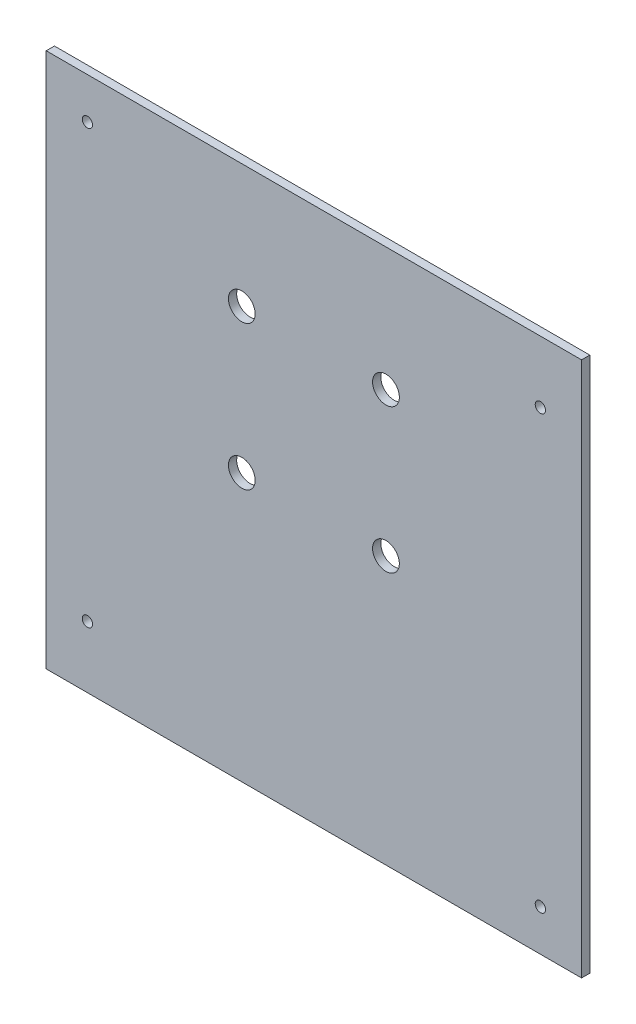
SolidWorks part; units mm, degrees
ref_plane "Спереди" through (0, 0, 0) normal (0, 0, 1) x (1, 0, 0)
ref_plane "Сверху" through (0, 0, 0) normal (0, 1, 0) x (1, 0, 0)
ref_plane "Справа" through (0, 0, 0) normal (1, 0, 0) x (0, 0, -1)
sketch "Эскиз1" plane through (0, 0, 0) normal (0, 0, 1) x (1, 0, 0)
  line L1 (-65, -82.5) -> (65, -82.5)
  line L2 (-65, -82.5) -> (-65, 47.5)
  line L3 (-65, 47.5) -> (65, 47.5)
  line L4 (65, -82.5) -> (65, 47.5)
  circle A0 centre (-55, 37.5) radius 1.25
  circle A1 centre (55, 32.5) radius 1.25
  circle A2 centre (55, -72.5) radius 1.25
  circle A3 centre (-55, -67.5) radius 1.25
  circle A4 centre (-17.5, 17.5) radius 3.25
  circle A5 centre (17.5, 17.5) radius 3.25
  circle A6 centre (-17.5, -17.5) radius 3.25
  circle A7 centre (17.5, -17.5) radius 3.25
  point P0 (0, 0)
  dimension "D3" = 2.5
  dimension "D4" = 2.5
  dimension "D5" = 2.5
  dimension "D6" = 2.5
  dimension "D8" = 10
  dimension "D9" = 10
  dimension "D11" = 10
  dimension "D12" = 10
  dimension "D13" = 10
  dimension "D14" = 15
  dimension "D15" = 35
  dimension "D16" = 35
  dimension "D17" = 6.5
  dimension "D18" = 6.5
  dimension "D19" = 6.5
  dimension "D20" = 6.5
  dimension "D21" = 35
  dimension "D22" = 35
  dimension "D23" = 47.5
  dimension "D24" = 47.5
  dimension "D25" = 30
  dimension "D26" = 47.5
  dimension "D1" = 130
  dimension "D2" = 130
  dimension "D7" = 10
  dimension "D10" = 15
  dimension "D27" = 65
extrude "Бобышка-Вытянуть1" add sketch "Эскиз1" along normal blind 2
